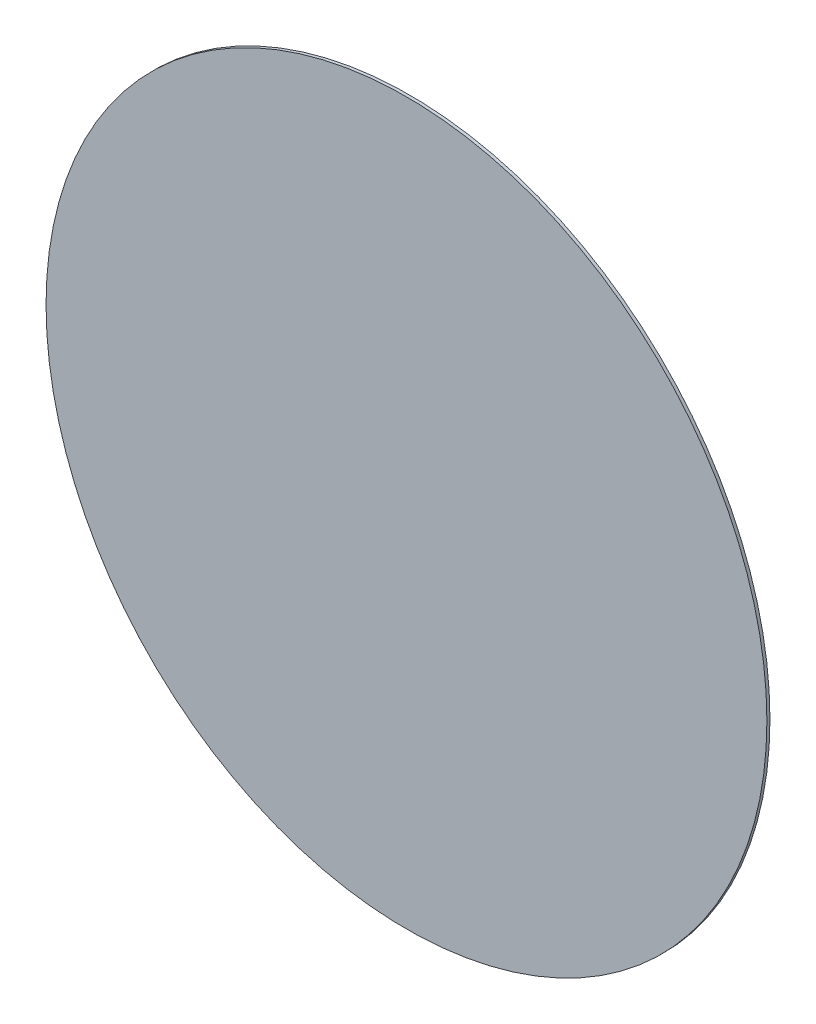
SolidWorks part; units mm, degrees
material "1023 Carbon Steel Sheet (SS)"
ref_plane "Front Plane" through (0, 0, 0) normal (0, 0, 1) x (1, 0, 0)
ref_plane "Top Plane" through (0, 0, 0) normal (0, 1, 0) x (1, 0, 0)
ref_plane "Right Plane" through (0, 0, 0) normal (1, 0, 0) x (0, 0, -1)
sketch "Sketch1" plane through (0, 0, 0) normal (0, 0, 1) x (1, 0, 0)
  circle A1 centre (0, 0) radius 59
  dimension "D1" = 118
extrude "Boss-Extrude1" add sketch "Sketch1" along normal blind 0.5
